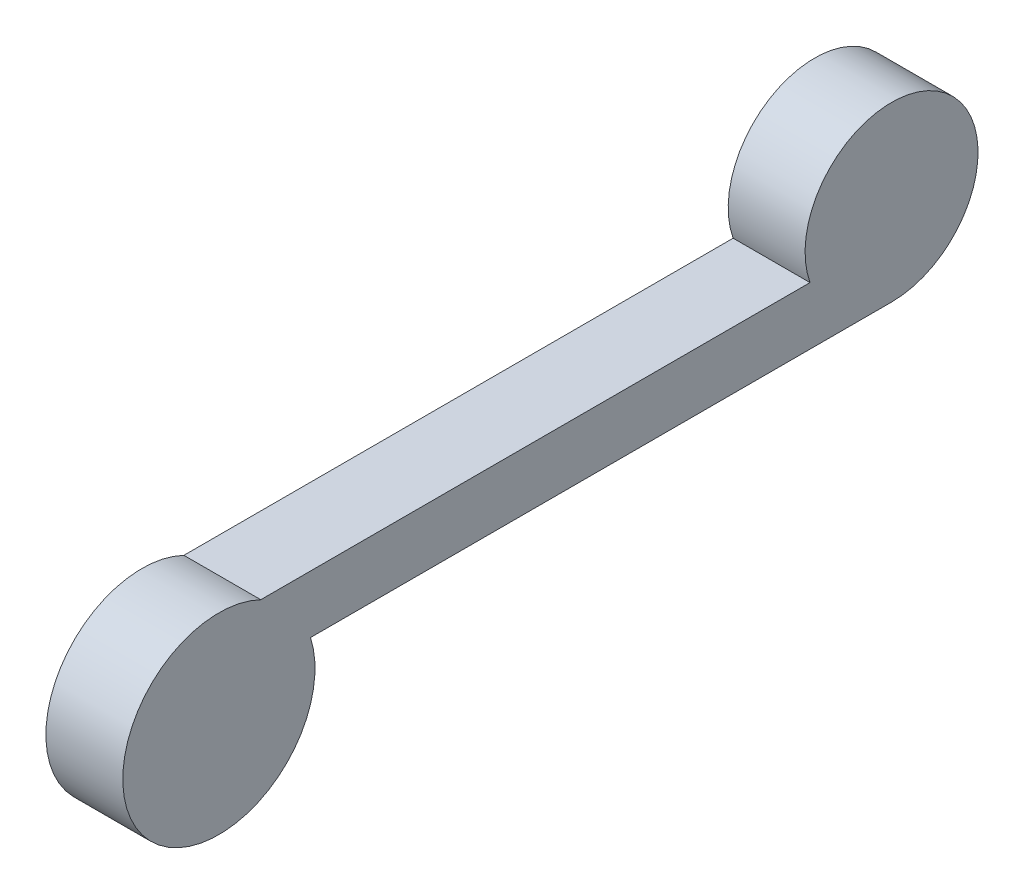
SolidWorks part; units mm, degrees
ref_plane "Front Plane" through (0, 0, 0) normal (0, 0, 1) x (1, 0, 0)
ref_plane "Top Plane" through (0, 0, 0) normal (0, 1, 0) x (1, 0, 0)
ref_plane "Right Plane" through (0, 0, 0) normal (1, 0, 0) x (0, 0, -1)
sketch "Sketch1" plane through (0, 0, 0) normal (1, 0, 0) x (0, 0, -1)
  line L0 (0, 0) -> (0, 15) construction
  line L2 (0, 15) -> (350, 15)
  line L3 (0, 15) -> (0, 45)
  line L4 (0, 45) -> (350, 45)
  line L5 (350, 15) -> (350, 45)
  circle A0 centre (0, 0) radius 50
  circle A1 centre (350, 60) radius 45
  dimension "D1" = 100
  dimension "D2" = 15
  dimension "D3" = 30
  dimension "D4" = 350
extrude "Boss-Extrude1" add sketch "Sketch1" along normal mid plane 40
